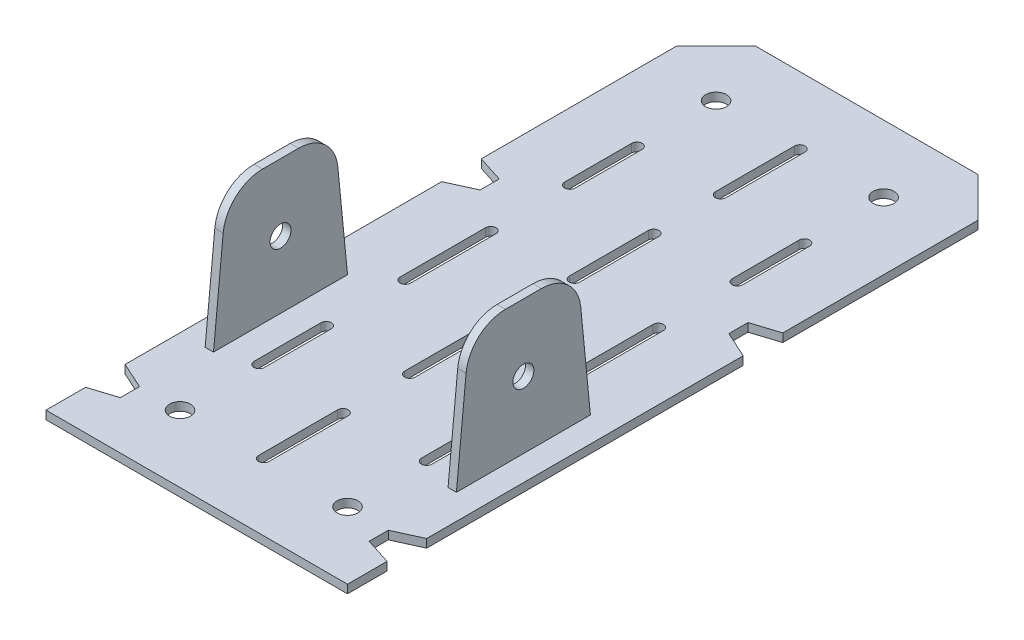
SolidWorks part; units mm, degrees
ref_plane "Front Plane" through (0, 0, 0) normal (0, 0, 1) x (1, 0, 0)
ref_plane "Top Plane" through (0, 0, 0) normal (0, 1, 0) x (1, 0, 0)
ref_plane "Right Plane" through (0, 0, 0) normal (1, 0, 0) x (0, 0, -1)
sketch "Sketch1" plane through (0, 0, 0) normal (0, 1, 0) x (1, 0, 0)
  line L1 (-57.15, 127) -> (57.15, 127)
  line L2 (-57.15, 127) -> (-57.15, -127)
  line L3 (-57.15, -127) -> (57.15, -127)
  line L4 (57.15, 127) -> (57.15, -127)
  line L5 (-57.15, 127) -> (57.15, -127) construction
  line L6 (-57.15, -127) -> (57.15, 127) construction
  point P0 (0, 0)
extrude "Boss-Extrude1" add sketch "Sketch1" along normal mid plane 3.175
sketch "Sketch2" plane through (0, 1.5875, 0) normal (0, 1, 0) x (1, 0, 0)
  line L0 (0, 0) -> (0, -126.9977) construction
  line L1 (-57.15, -127) -> (57.15, -127) construction
  line L2 (44.45, -25.4) -> (47.625, -25.4)
  line L3 (44.45, -25.4) -> (44.45, -76.2)
  line L4 (44.45, -76.2) -> (47.625, -76.2)
  line L5 (47.625, -25.4) -> (47.625, -76.2)
  line L6 (-47.625, -25.4) -> (-47.625, -76.2)
  line L7 (-44.45, -76.2) -> (-47.625, -76.2)
  line L8 (-44.45, -25.4) -> (-44.45, -76.2)
  line L9 (-44.45, -25.4) -> (-47.625, -25.4)
  dimension "D1" = 44.45
  dimension "D2" = 50.8
  dimension "D3" = 50.8
extrude "Boss-Extrude2" add sketch "Sketch2" along normal blind 50.8
sketch "Sketch3" plane through (0, 0, 0) normal (1, 0, 0) x (0, 0, -1)
  line L0 (-25.4, 1.5875) -> (-25.4, 52.3875)
  line L1 (-25.4, 52.3875) -> (-30.4, 52.3875)
  line L2 (-76.2, 52.3875) -> (-25.4, 52.3875) construction
  line L3 (-30.4, 52.3875) -> (-25.4, 1.5875)
  line L4 (-76.2, 52.3875) -> (-71.2, 52.3875)
  line L5 (-76.2, 52.3875) -> (-76.2, 1.5875)
  line L6 (-76.2, 1.5875) -> (-71.2, 52.3875)
extrude "Cut-Extrude1" cut sketch "Sketch3" against normal mid plane 100
sketch "Sketch4" plane through (0, 0, 0) normal (1, 0, 0) x (0, 0, -1)
  line L0 (-127, 1.5875) -> (127, 1.5875) construction
  circle A0 centre (-50.8, 26.9875) radius 3.9687
  dimension "D1" = 25.4
extrude "Cut-Extrude2" cut sketch "Sketch4" against normal mid plane 100
sketch "Sketch5" plane through (0, 1.5875, 0) normal (0, 1, 0) x (1, 0, 0)
  line L0 (57.15, -127) -> (57.15, 127) construction
  line L1 (-57.15, 127) -> (-57.15, -127) construction
  line L2 (-57.15, -127) -> (57.15, -127) construction
  line L3 (57.15, 127) -> (-57.15, 127) construction
  line L4 (0, -101.6) -> (0, -71.6) construction
  line L5 (-1.9844, -101.6) -> (-1.9844, -71.6)
  line L6 (1.9844, -101.6) -> (1.9844, -71.6)
  line L7 (0, -46.2) -> (0, -16.2) construction
  line L8 (-1.9844, -46.2) -> (-1.9844, -16.2)
  line L9 (1.9844, -46.2) -> (1.9844, -16.2)
  line L10 (0, 16.2) -> (0, 46.2) construction
  line L11 (-1.9844, 16.2) -> (-1.9844, 46.2)
  line L12 (1.9844, 16.2) -> (1.9844, 46.2)
  line L13 (0, 71.6) -> (0, 101.6) construction
  line L14 (-1.9844, 71.6) -> (-1.9844, 101.6)
  line L15 (1.9844, 71.6) -> (1.9844, 101.6)
  line L16 (0, -46.2) -> (31.75, -46.2) construction
  line L17 (31.75, -46.2) -> (31.75, -71.6) construction
  line L18 (31.75, -71.6) -> (0, -71.6) construction
  line L19 (31.75, -46.2) -> (31.75, -71.6) construction
  line L20 (33.7344, -46.2) -> (33.7344, -71.6)
  line L21 (29.7656, -46.2) -> (29.7656, -71.6)
  line L22 (0, 16.2) -> (0, -16.2) construction
  line L23 (0, -16.2) -> (31.75, -16.2) construction
  line L24 (31.75, -16.2) -> (31.75, 16.2) construction
  line L25 (31.75, 16.2) -> (0, 16.2) construction
  line L26 (31.75, 16.2) -> (31.75, -16.2) construction
  line L27 (33.7344, 16.2) -> (33.7344, -16.2)
  line L28 (29.7656, 16.2) -> (29.7656, -16.2)
  line L29 (0, 71.6) -> (31.75, 71.6) construction
  line L30 (31.75, 71.6) -> (31.75, 46.2) construction
  line L31 (31.75, 71.6) -> (31.75, 46.2) construction
  line L32 (33.7344, 71.6) -> (33.7344, 46.2)
  line L33 (29.7656, 71.6) -> (29.7656, 46.2)
  line L34 (-31.75, -46.2) -> (-31.75, -71.6) construction
  line L35 (-29.7656, -46.2) -> (-29.7656, -71.6)
  line L36 (-33.7344, -46.2) -> (-33.7344, -71.6)
  line L37 (-31.75, 16.2) -> (-31.75, -16.2) construction
  line L38 (-29.7656, 16.2) -> (-29.7656, -16.2)
  line L39 (-33.7344, 16.2) -> (-33.7344, -16.2)
  line L40 (-31.75, 71.6) -> (-31.75, 46.2) construction
  line L41 (-29.7656, 71.6) -> (-29.7656, 46.2)
  line L42 (-33.7344, 71.6) -> (-33.7344, 46.2)
  line L43 (57.15, 38) -> (57.15, 23)
  line L44 (57.15, 38) -> (47.15, 34.8124)
  line L45 (47.15, 34.8124) -> (47.15, 27.5502)
  line L46 (47.15, 27.5502) -> (57.15, 23)
  line L47 (0, 127) -> (0, 111.1901) construction
  line L48 (-47.15, 27.5502) -> (-57.15, 23)
  line L49 (-47.15, 34.8124) -> (-47.15, 27.5502)
  line L50 (-57.15, 38) -> (-47.15, 34.8124)
  line L51 (-57.15, 38) -> (-57.15, 23)
  line L52 (57.15, -37) -> (82.407, -37) construction
  line L53 (47.15, -101.5502) -> (57.15, -97)
  line L54 (47.15, -108.8124) -> (47.15, -101.5502)
  line L55 (57.15, -112) -> (47.15, -108.8124)
  line L56 (57.15, -112) -> (57.15, -97)
  line L57 (-57.15, -112) -> (-57.15, -97)
  line L58 (-57.15, -112) -> (-47.15, -108.8124)
  line L59 (-47.15, -108.8124) -> (-47.15, -101.5502)
  line L60 (-47.15, -101.5502) -> (-57.15, -97)
  circle A0 centre (31.75, -101.6) radius 3.9687
  circle A1 centre (-31.75, -101.6) radius 3.9687
  circle A2 centre (31.75, 101.6) radius 3.9687
  circle A3 centre (-31.75, 101.6) radius 3.9687
  circle A4 centre (0, 0) radius 3.9687
  arc A5 (-1.9844, -101.6) -> (1.9844, -101.6) centre (0, -101.6) ccw
  arc A6 (1.9844, -71.6) -> (-1.9844, -71.6) centre (0, -71.6) ccw
  arc A7 (-1.9844, -46.2) -> (1.9844, -46.2) centre (0, -46.2) ccw
  arc A8 (1.9844, -16.2) -> (-1.9844, -16.2) centre (0, -16.2) ccw
  arc A9 (-1.9844, 16.2) -> (1.9844, 16.2) centre (0, 16.2) ccw
  arc A10 (1.9844, 46.2) -> (-1.9844, 46.2) centre (0, 46.2) ccw
  arc A11 (-1.9844, 71.6) -> (1.9844, 71.6) centre (0, 71.6) ccw
  arc A12 (1.9844, 101.6) -> (-1.9844, 101.6) centre (0, 101.6) ccw
  arc A13 (33.7344, -46.2) -> (29.7656, -46.2) centre (31.75, -46.2) ccw
  arc A14 (29.7656, -71.6) -> (33.7344, -71.6) centre (31.75, -71.6) ccw
  arc A15 (33.7344, 16.2) -> (29.7656, 16.2) centre (31.75, 16.2) ccw
  arc A16 (29.7656, -16.2) -> (33.7344, -16.2) centre (31.75, -16.2) ccw
  arc A17 (33.7344, 71.6) -> (29.7656, 71.6) centre (31.75, 71.6) ccw
  arc A18 (29.7656, 46.2) -> (33.7344, 46.2) centre (31.75, 46.2) ccw
  arc A19 (-29.7656, -46.2) -> (-33.7344, -46.2) centre (-31.75, -46.2) ccw
  arc A20 (-33.7344, -71.6) -> (-29.7656, -71.6) centre (-31.75, -71.6) ccw
  arc A21 (-29.7656, 16.2) -> (-33.7344, 16.2) centre (-31.75, 16.2) ccw
  arc A22 (-33.7344, -16.2) -> (-29.7656, -16.2) centre (-31.75, -16.2) ccw
  arc A23 (-29.7656, 71.6) -> (-33.7344, 71.6) centre (-31.75, 71.6) ccw
  arc A24 (-33.7344, 46.2) -> (-29.7656, 46.2) centre (-31.75, 46.2) ccw
  point P21 (0, -86.6)
  point P28 (0, -31.2)
  point P35 (0, 31.2)
  point P42 (0, 86.6)
  point P49 (31.75, -58.9)
  point P60 (31.75, 0)
  point P65 (31.75, 58.9)
  point P75 (-31.75, -58.9)
  point P80 (-31.75, 0)
  point P87 (-31.75, 58.9)
  point P96 (57.15, 30.5)
  dimension "D1" = 25.4
  dimension "D8" = 30
  dimension "D10" = 30
  dimension "D12" = 30
  dimension "D14" = 25.4
  dimension "D16" = 10
  dimension "D2" = 25.4
  dimension "D3" = 25.4
  dimension "D4" = 25.4
  dimension "D5" = 25.4
  dimension "D6" = 25.4
  dimension "D7" = 127
  dimension "D9" = 25.4
  dimension "D11" = 25.4
  dimension "D13" = 16.2
  dimension "D15" = 30
  dimension "D17" = 150
  dimension "D18" = 15
  dimension "D19" = 90
extrude "Cut-Extrude3" cut sketch "Sketch5" against normal blind 100
chamfer "Chamfer1" distance 15 angle 45 2 edges at (-57.15, 0, -127) (57.15, 0, -127)
fillet "Fillet1" radius 15 4 edges at (-46.0375, 52.3875, 30.4) (-46.0375, 52.3875, 71.2) (46.0375, 52.3875, 30.4) (46.0375, 52.3875, 71.2)
